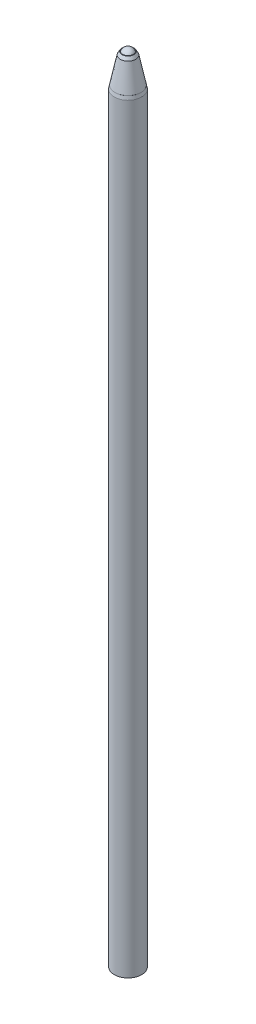
SolidWorks part; units mm, degrees
ref_plane "Frontal" through (0, 0, 0) normal (0, 0, 1) x (1, 0, 0)
ref_plane "Superior" through (0, 0, 0) normal (0, 1, 0) x (1, 0, 0)
ref_plane "Lateral" through (0, 0, 0) normal (1, 0, 0) x (0, 0, -1)
sketch "Sketch1" plane through (0, 0, 0) normal (1, 0, 0) x (0, 0, -1)
  line L0 (0.4, 12.669) -> (0.25, 12.7556)
  line L1 (0.45, 0) -> (0, 0)
  line L2 (3, -3.33) -> (3, -9.63) construction
  line L3 (3, -9.63) -> (3.25, -9.63) construction
  line L4 (1.175, 10.92) -> (1.175, -2.03)
  line L5 (0.66, 13.4515) -> (1.1136, 11.222)
  line L6 (0.505, 13.72) -> (0.4596, 13.72)
  line L7 (1.175, -2.03) -> (2.5, -2.03) construction
  line L8 (0.4, 12.669) -> (0.4, 8.89)
  line L9 (0.505, 13.72) -> (0.66, 13.4515)
  line L10 (0.25, 13.0666) -> (0.25, 12.7556)
  line L11 (0, 13.7949) -> (0, -76.1005) construction
  line L12 (0.45, 8.84) -> (0.45, 0)
  line L13 (0.45, 8.84) -> (0.4, 8.89)
  line L14 (0.25, 13.0666) -> (0.5, 13.211)
  line L15 (0.5, 13.65) -> (0.5, 13.211)
  line L16 (0.5, 13.65) -> (0.4596, 13.72)
  line L17 (3.25, -9.63) -> (3.3358, -47.03) construction
  line L18 (3.3358, -47.03) -> (4.655, -47.03) construction
  line L19 (4.655, -47.03) -> (4.655, -47.71) construction
  line L20 (4.655, -47.71) -> (3.3373, -47.71) construction
  line L21 (3.3412, -49.41) -> (4.655, -49.41) construction
  line L22 (4.655, -49.41) -> (4.655, -50.09) construction
  line L23 (4.655, -50.09) -> (3.3428, -50.09) construction
  line L24 (3.3373, -47.71) -> (3.3412, -49.41) construction
  line L25 (3.3428, -50.09) -> (3.4, -75.03) construction
  line L26 (3.4, -75.03) -> (0, -75.03) construction
  line L27 (0, 0) -> (0, -75.03) construction
  line L28 (1.114, 11.22) -> (1.111, 11.22)
  line L29 (1.1136, 11.222) -> (1.111, 11.22)
  line L30 (1.114, 11.22) -> (1.175, 10.92)
  line L31 (2.5, -2.03) -> (2.5, -3.33) construction
  line L32 (2.5, -3.33) -> (3, -3.33) construction
  line L33 (2.5, -3.33) -> (2.5, -9.63) construction
  line L34 (2.5, -9.63) -> (3.25, -9.63) construction
  line L35 (1.175, -2.03) -> (1.175, -54.11)
  line L36 (1.175, -54.11) -> (0, -54.11)
  line L37 (0, -54.11) -> (0, 0)
  dimension "D4" = 0.2685
  dimension "D18" = 60
  dimension "D15" = 1.01
  dimension "D21" = 0.4596
  dimension "D2" = 45
  dimension "D3" = 1.175
  dimension "D5" = 0.5
  dimension "D6" = 12.669
  dimension "D7" = 13.72
  dimension "D8" = 2.8
  dimension "D9" = 1.32
  dimension "D10" = 11.499
  dimension "D11" = 8.84
  dimension "D12" = 2.5
  dimension "D13" = 8.89
  dimension "D14" = 3
  dimension "D16" = 0.45
  dimension "D17" = 0.4
  dimension "D19" = 0.6534
  dimension "D20" = 30
  dimension "D22" = 60
  dimension "D23" = 0.07
  dimension "D24" = 30
  dimension "D25" = 15.75
  dimension "D26" = 7.6
  dimension "D27" = 6.5
  dimension "D28" = 6.8
  dimension "D29" = 73
  dimension "D30" = 4.655
  dimension "D31" = 0.68
  dimension "D32" = 0.68
  dimension "D33" = 1.7
  dimension "D34" = 52.08
  dimension "D35" = 2.5
revolve "Revolve2" add sketch "Sketch1" angle 360 about L11
sketch "Esboço1" plane through (0, 0, 0) normal (0, 0, 1) x (1, 0, 0)
  line L0 (0, 13) -> (0, 14)
  line L1 (0, 13.5) -> (0.2748, 13.5) construction
  arc A0 (0, 14) -> (0, 13) centre (0, 13.5) ccw
  dimension "D1" = 0.5
revolve "Revolução1" add sketch "Esboço1" angle 360 about L0
